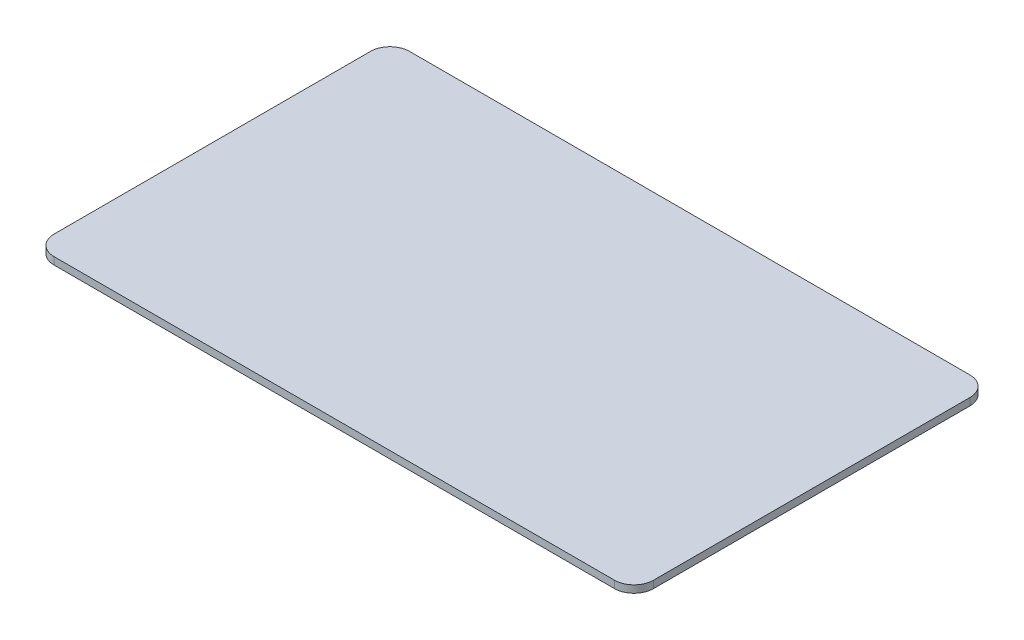
SolidWorks part; units mm, degrees
material "Acrílico (Impacto medio-alto)"
ref_plane "Alzado" through (0, 0, 0) normal (0, 0, 1) x (1, 0, 0)
ref_plane "Planta" through (0, 0, 0) normal (0, 1, 0) x (1, 0, 0)
ref_plane "Vista lateral" through (0, 0, 0) normal (1, 0, 0) x (0, 0, -1)
sketch "Croquis1" plane through (0, 0, 0) normal (0, 1, 0) x (1, 0, 0)
  line L1 (-114.85, -72.85) -> (114.85, -72.85)
  line L2 (-122.85, -64.85) -> (-122.85, 64.85)
  line L3 (-114.85, 72.85) -> (114.85, 72.85)
  line L4 (122.85, -64.85) -> (122.85, 64.85)
  line L5 (-122.85, -72.85) -> (122.85, 72.85) construction
  line L6 (-122.85, 72.85) -> (122.85, -72.85) construction
  arc A0 (-114.85, -72.85) -> (-122.85, -64.85) centre (-114.85, -64.85) cw
  arc A1 (114.85, -72.85) -> (122.85, -64.85) centre (114.85, -64.85) ccw
  arc A2 (114.85, 72.85) -> (122.85, 64.85) centre (114.85, 64.85) cw
  arc A3 (-122.85, 64.85) -> (-114.85, 72.85) centre (-114.85, 64.85) cw
  point P0 (0, 0)
  dimension "D3" = 8
  dimension "D1" = 245.7
  dimension "D2" = 145.7
extrude "Saliente-Extruir1" add sketch "Croquis1" along normal mid plane 3
